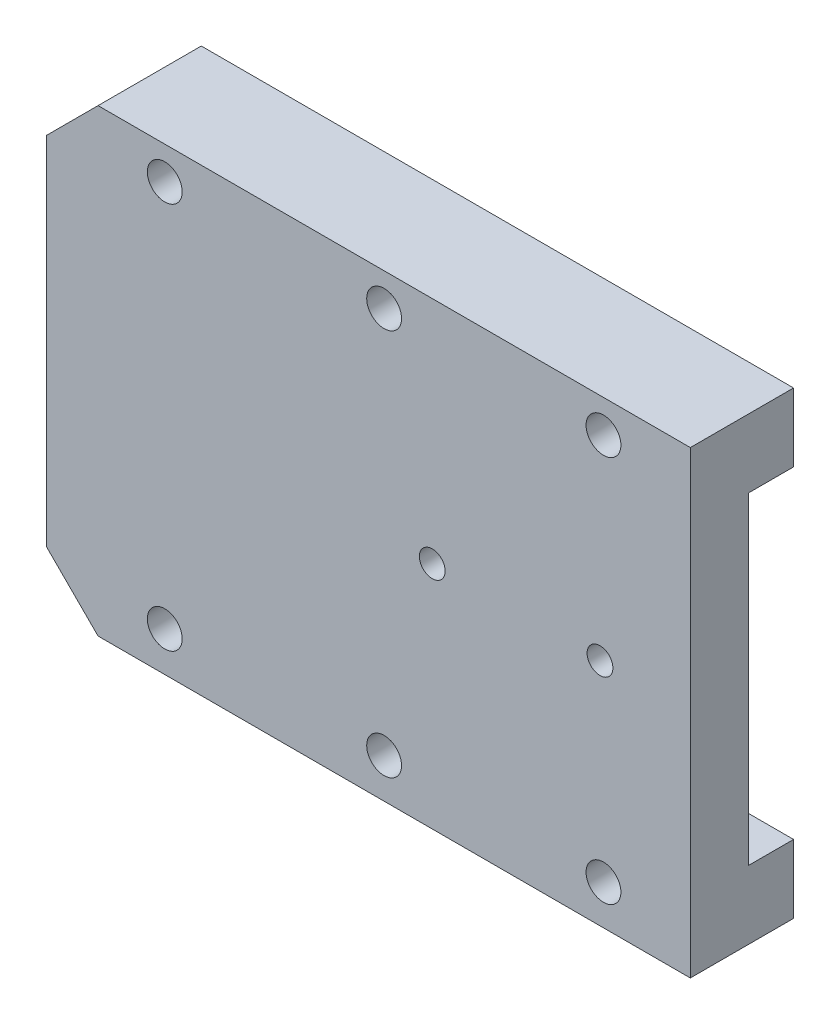
SolidWorks part; units mm, degrees
ref_plane "Ön Düzlem" through (0, 0, 0) normal (0, 0, 1) x (1, 0, 0)
ref_plane "Üst Düzlem" through (0, 0, 0) normal (0, 1, 0) x (1, 0, 0)
ref_plane "Sağ Düzlem" through (0, 0, 0) normal (1, 0, 0) x (0, 0, -1)
sketch "Sketch1" plane through (0, 0, 0) normal (0, 0, 1) x (1, 0, 0)
  line L1 (22.5, 17.8) -> (-22.5, 17.8)
  line L2 (22.5, 17.8) -> (22.5, -17.8)
  line L3 (22.5, -17.8) -> (-22.5, -17.8)
  line L4 (-22.5, 17.8) -> (-22.5, -17.8)
  line L5 (22.5, 17.8) -> (-22.5, -17.8) construction
  line L6 (22.5, -17.8) -> (-22.5, 17.8) construction
  point P0 (0, 0)
  dimension "D1" = 45
  dimension "D2" = 35.6
extrude "Boss-Extrude1" add sketch "Sketch1" along normal mid plane 8
sketch "Sketch2" plane through (0, 0, -4) normal (0, 0, -1) x (-1, 0, 0)
  circle A0 centre (-15.7694, -14.7329) radius 1.35
  circle A1 centre (1.2306, -14.7329) radius 1.35
  circle A2 centre (18.2306, -14.7329) radius 1.35
  circle A3 centre (18.2306, 15.2671) radius 1.35
  circle A4 centre (1.2306, 15.2671) radius 1.35
  circle A5 centre (-15.7694, 15.2671) radius 1.35
extrude "Cut-Extrude1" cut sketch "Sketch2" against normal through all
sketch "Sketch3" plane through (0, 0, -4) normal (0, 0, -1) x (-1, 0, 0)
  line L0 (-22.5, 17.8) -> (22.5, 17.8) construction
  line L1 (27.4, 17.8) -> (22.5, 17.8)
  line L2 (27.4, 17.8) -> (27.4, -17.8)
  line L3 (27.4, -17.8) -> (22.5, -17.8)
  line L4 (22.5, 17.8) -> (22.5, -17.8)
  line L5 (27.4, 17.8) -> (22.5, -17.8) construction
  line L6 (27.4, -17.8) -> (22.5, 17.8) construction
  line L7 (22.5, -17.8) -> (-22.5, -17.8) construction
  line L8 (22.5, 17.8) -> (22.5, -17.8) construction
  point P0 (24.95, 0)
  dimension "D1" = 4.9
extrude "Boss-Extrude2" add sketch "Sketch3" against normal up to surface (8 mm away) up to face at (14.4194, 15.2671, 4)
chamfer "Chamfer1" distance 4 angle 45 2 edges at (-27.4, 17.8, 0) (-27.4, -17.8, 0)
sketch "Sketch5" plane through (-27.4, 0, 0) normal (-1, 0, 0) x (0, 0, 1)
  line L1 (-0.5, 12.5) -> (-4, 12.5)
  line L2 (-0.5, 12.5) -> (-0.5, -12.5)
  line L3 (-0.5, -12.5) -> (-4, -12.5)
  line L4 (-4, 12.5) -> (-4, -12.5)
  line L5 (-0.5, 12.5) -> (-4, -12.5) construction
  line L6 (-0.5, -12.5) -> (-4, 12.5) construction
  line L7 (-4, -13.8) -> (-4, 13.8) construction
  point P0 (-2.25, 0)
  dimension "D1" = 25
  dimension "D2" = 3.5
extrude "Cut-Extrude2" cut sketch "Sketch5" against normal through all
sketch "Sketch6" plane through (0, 0, 4) normal (0, 0, 1) x (1, 0, 0)
  line L2 (0, 0) -> (22.5, 0) construction
  line L3 (22.5, -17.8) -> (22.5, 17.8) construction
  circle A2 centre (2.5, 0) radius 1
  circle A3 centre (15.5, 0) radius 1
  dimension "D6" = 2
  dimension "D4" = 7
  dimension "D5" = 20
extrude "Cut-Extrude4" cut sketch "Sketch6" against normal through all
